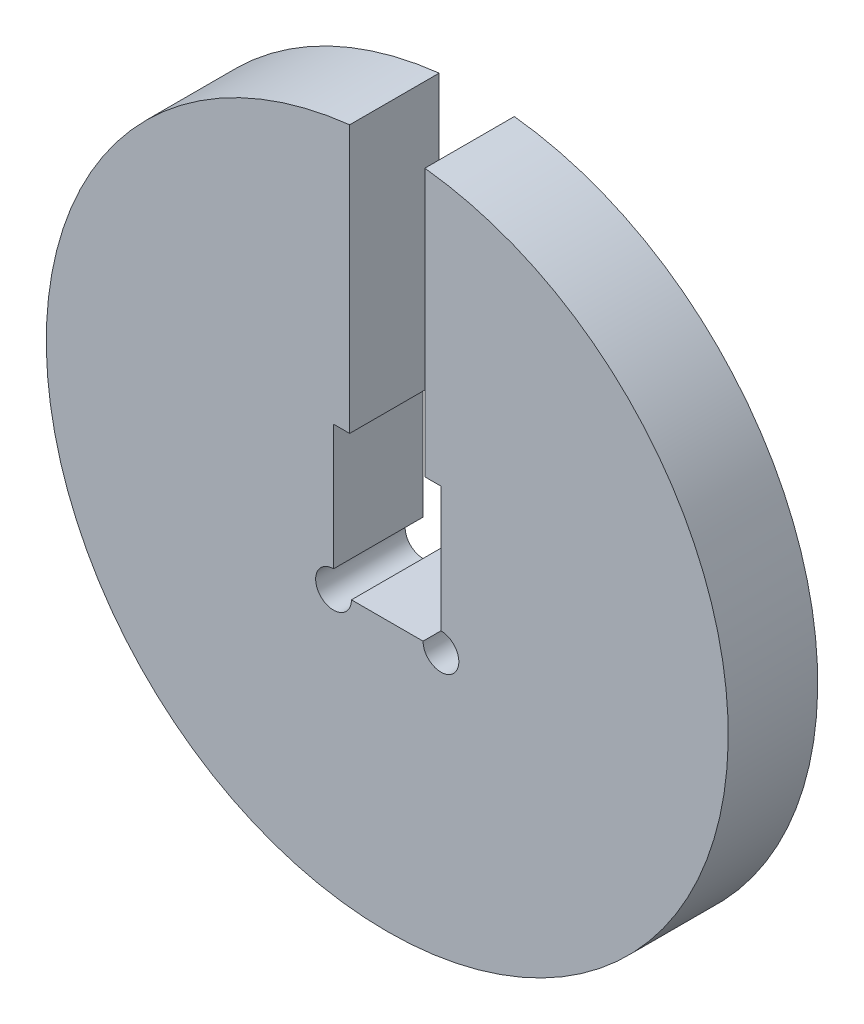
SolidWorks part; units mm, degrees
material "ABS PC"
ref_plane "Front Plane" through (0, 0, 0) normal (0, 0, 1) x (1, 0, 0)
ref_plane "Top Plane" through (0, 0, 0) normal (0, 1, 0) x (1, 0, 0)
ref_plane "Right Plane" through (0, 0, 0) normal (1, 0, 0) x (0, 0, -1)
sketch "Sketch1" plane through (0, 0, 0) normal (0, 0, 1) x (1, 0, 0)
  line L0 (0, 0) -> (0, 2) construction
  line L1 (0, 0) -> (0, -2) construction
  line L3 (-1.5, 2) -> (1.5, 2)
  line L4 (-1.5, 2) -> (-1.5, -2)
  line L5 (-1.5, -2) -> (1.5, -2)
  line L6 (1.5, 2) -> (1.5, -2)
  circle A0 centre (0, 0) radius 9.525
  dimension "D3" = 19.05
  dimension "D1" = 3
  dimension "D2" = 4
extrude "Boss-Extrude1" add sketch "Sketch1" along normal blind 2.5
sketch "Sketch2" plane through (0, 0, 2.5) normal (0, 0, 1) x (1, 0, 0)
  line L0 (0, 9.525) -> (0, 2) construction
  line L1 (-1.05, 2) -> (1.05, 2)
  line L2 (-1.05, 2) -> (-1.05, 9.525)
  line L3 (-1.05, 9.525) -> (1.05, 9.525)
  line L4 (1.05, 2) -> (1.05, 9.525)
  line L5 (1.5, 2) -> (-1.5, 2) construction
  circle A1 centre (-1.5, -2) radius 0.5
  circle A2 centre (1.5, -2) radius 0.5
  circle A4 centre (0, 0) radius 9.525 construction
  dimension "D1" = 2.1
extrude "Cut-Extrude1" cut sketch "Sketch2" against normal through all
